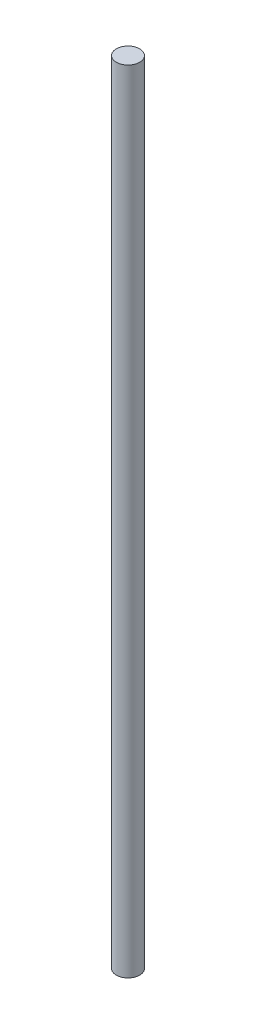
SolidWorks part; units mm, degrees
ref_plane "Alzado" through (0, 0, 0) normal (0, 0, 1) x (1, 0, 0)
ref_plane "Planta" through (0, 0, 0) normal (0, 1, 0) x (1, 0, 0)
ref_plane "Vista lateral" through (0, 0, 0) normal (1, 0, 0) x (0, 0, -1)
sketch "Croquis1" plane through (0, 0, 0) normal (0, 1, 0) x (1, 0, 0)
  circle A0 centre (0, 0) radius 1.55
  dimension "D1" = 3.1
extrude "Saliente-Extruir1" add sketch "Croquis1" along normal blind 105
